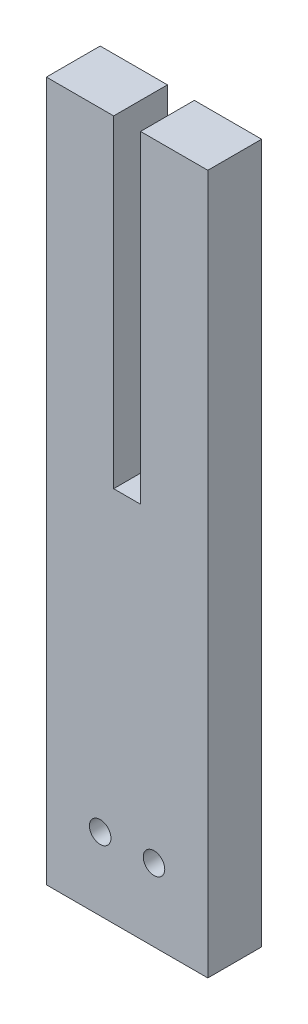
SolidWorks part; units mm, degrees
ref_plane "Plano frontal" through (0, 0, 0) normal (0, 0, 1) x (1, 0, 0)
ref_plane "Plano superior" through (0, 0, 0) normal (0, 1, 0) x (1, 0, 0)
ref_plane "Plano direito" through (0, 0, 0) normal (1, 0, 0) x (0, 0, -1)
sketch "Esboço1" plane through (0, 0, 0) normal (0, 0, 1) x (1, 0, 0)
  line L0 (15, 70) -> (-15, -70) construction
  line L1 (-15, 70) -> (15, 70)
  line L2 (-15, 70) -> (-15, -70)
  line L3 (-15, -70) -> (15, -70)
  line L4 (15, 70) -> (15, -70)
  line L5 (-15, -70) -> (-15, -70.6761) construction
  dimension "D1" = 140
  dimension "D2" = 30
extrude "Ressalto-extrusão1" add sketch "Esboço1" along normal blind 10
sketch "Esboço2" plane through (0, 0, 10) normal (0, 0, 1) x (1, 0, 0)
  line L0 (-15, -43) -> (15, -43) construction
  line L1 (-15, 70) -> (-15, -70) construction
  line L2 (15, -70) -> (15, 70) construction
  line L3 (-5, -56.5) -> (5, -56.5) construction
  line L4 (-15, -70) -> (15, -70) construction
  line L5 (-5, -43) -> (-5, -56.5) construction
  circle A0 centre (-5, -56.5) radius 2
  circle A1 centre (5, -56.5) radius 2
  dimension "D2" = 4
  dimension "D4" = 4
  dimension "D1" = 27
  dimension "D3" = 10
  dimension "D5" = 10
  dimension "D6" = 13.5
extrude "Corte-extrusão1" cut sketch "Esboço2" against normal up to next
sketch "Esboço3" plane through (15, 0, 0) normal (1, 0, 0) x (0, 0, -1)
  line L0 (0, -70) -> (0, 70) construction
  line L1 (-10, 70) -> (0, 70)
  line L2 (-10, 70) -> (-10, 60)
  line L3 (-10, 60) -> (0, 60)
  line L4 (0, 70) -> (0, 60)
  dimension "D1" = 10
extrude "Corte-extrusão2" cut sketch "Esboço3" against normal up to next
sketch "Esboço4" plane through (0, 0, 10) normal (0, 0, 1) x (1, 0, 0)
  line L0 (-15, 60) -> (15, 60) construction
  line L1 (-2.5, 60) -> (2.5, 60)
  line L2 (-2.5, 60) -> (-2.5, 0)
  line L3 (-2.5, 0) -> (2.5, 0)
  line L4 (2.5, 60) -> (2.5, 0)
  dimension "D1" = 2.5
  dimension "D2" = 5
  dimension "D3" = 60
extrude "Corte-extrusão3" cut sketch "Esboço4" against normal up to next
